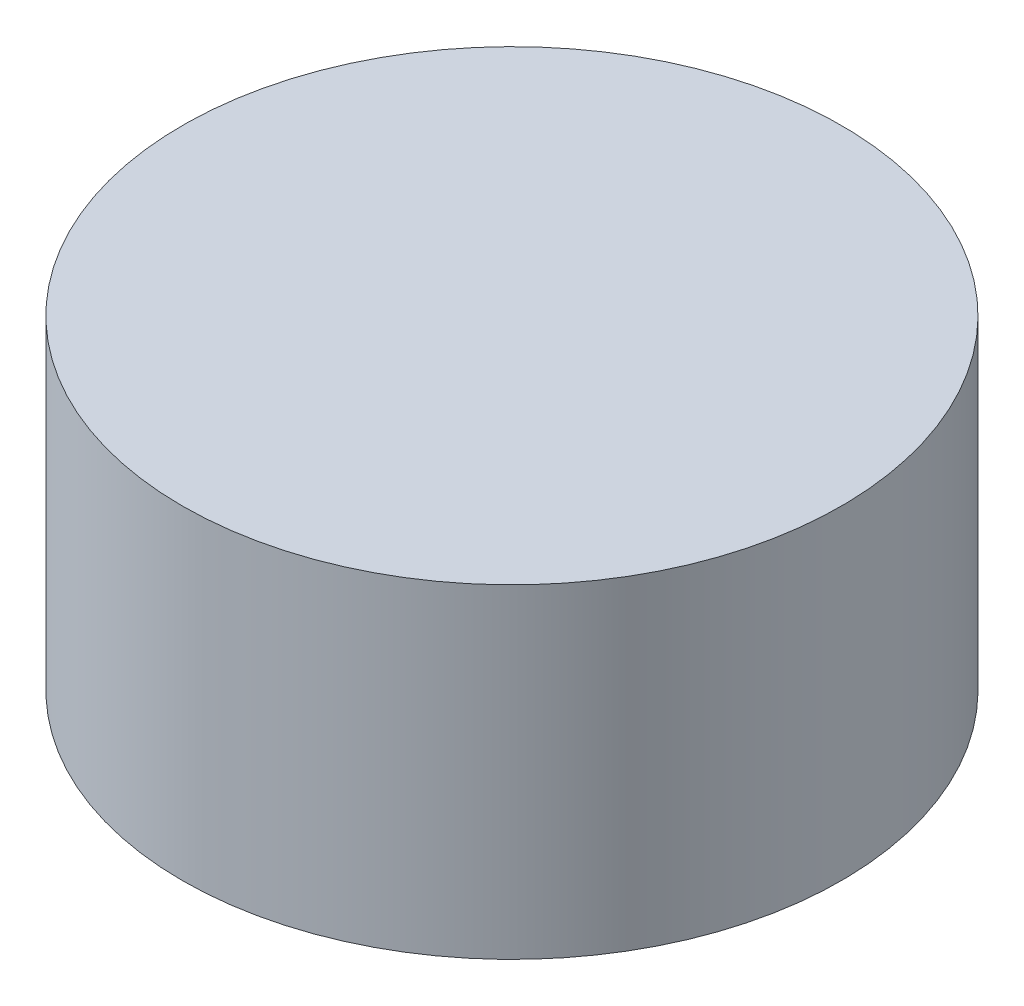
SolidWorks part; units mm, degrees
ref_plane "Front Plane" through (0, 0, 0) normal (0, 0, 1) x (1, 0, 0)
ref_plane "Top Plane" through (0, 0, 0) normal (0, 1, 0) x (1, 0, 0)
ref_plane "Right Plane" through (0, 0, 0) normal (1, 0, 0) x (0, 0, -1)
sketch "Sketch1" plane through (0, 0, 0) normal (0, 1, 0) x (1, 0, 0)
  circle A0 centre (0, 0) radius 3.2
  dimension "D1" = 6.4
extrude "Boss-Extrude1" add sketch "Sketch1" along normal blind 3.15
